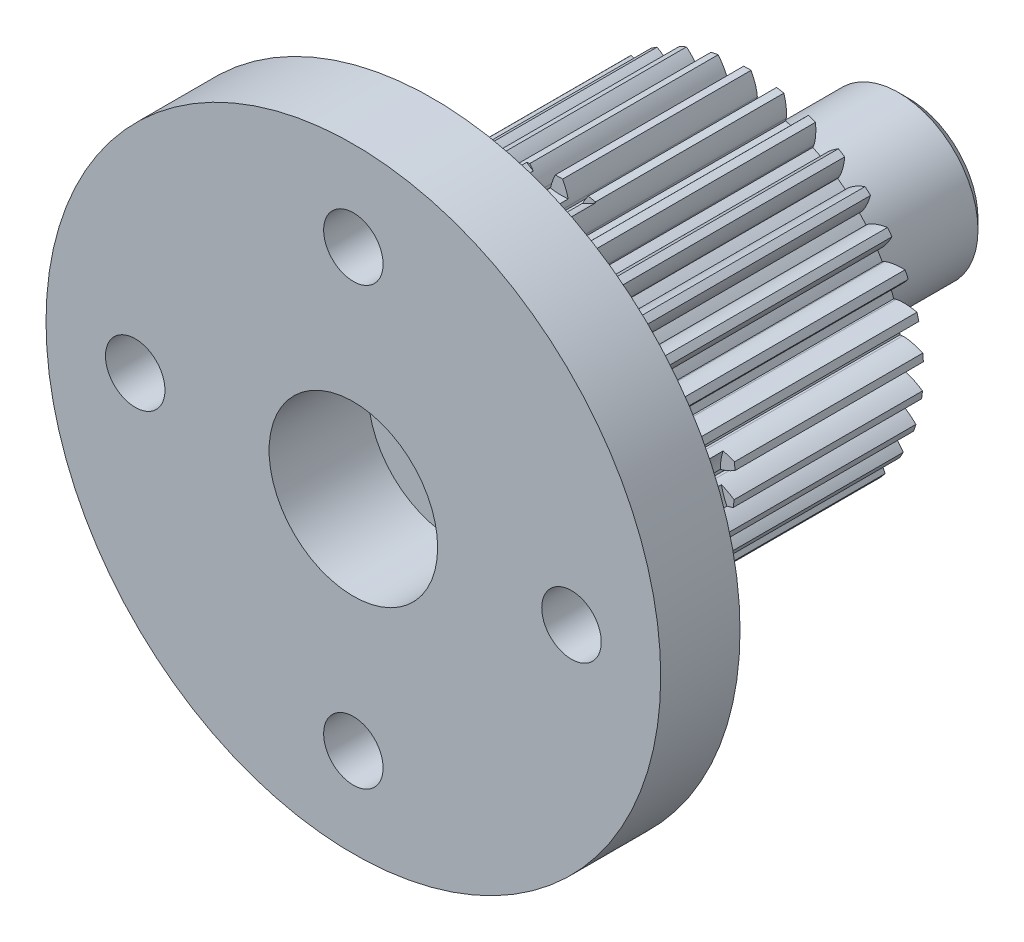
SolidWorks part; units mm, degrees
material "ABS"
ref_plane "Front Plane" through (0, 0, 0) normal (0, 0, 1) x (1, 0, 0)
ref_plane "Top Plane" through (0, 0, 0) normal (0, 1, 0) x (1, 0, 0)
ref_plane "Right Plane" through (0, 0, 0) normal (1, 0, 0) x (0, 0, -1)
sketch "Sketch1" plane through (0, 0, 0) normal (0, 0, 1) x (1, 0, 0)
  circle A0 centre (0, 0) radius 8.75
  dimension "D1" = 17.5
extrude "Boss-Extrude1" add sketch "Sketch1" along normal mid plane 16
sketch "Sketch2" plane through (0, 0, 0) normal (0, 0, 1) x (1, 0, 0)
  line L0 (0, 0) -> (7.7525, 0) construction
  line L1 (0, 0) -> (8.2456, -0.2697) construction
  line L2 (0, 0) -> (7.7359, -0.5066) construction
  line L3 (7.7525, 0) -> (7.625, 0)
  line L4 (7.7359, -0.5066) -> (7.6087, -0.4983)
  circle A0 centre (0, 0) radius 8.25 construction
  circle A1 centre (0, 0) radius 7.7525 construction
  circle A2 centre (0, 0) radius 7.625
  circle A3 centre (0, 0) radius 8.75 construction
  circle A4 centre (0, 0) radius 8.75
  spline S0 degree 4 poles (7.7525, 0) (7.7551, 0) (7.7625, 0.0003) (7.7855, 0.0017) (7.8306, 0.0067) (7.8861, 0.016) (7.9497, 0.0296) (8.0107, 0.045) (8.0626, 0.0595) (8.1142, 0.0754) (8.1654, 0.0924) (8.2271, 0.1143) (8.3008, 0.1426) (8.3862, 0.1784) (8.4823, 0.2223) (8.5793, 0.2706) (8.674, 0.3209) (8.7687, 0.375) (8.8596, 0.4297) (8.9529, 0.4897) (9.0385, 0.5468) (9.1331, 0.6144) (9.2091, 0.67) (9.3078, 0.7471) (9.3656, 0.7937) (9.4328, 0.8496) (9.4624, 0.8751) (9.4806, 0.8908) knots 0 0 0 0 0 0.005377 0.015084 0.04661 0.092111 0.119476 0.146842 0.174209 0.201575 0.228941 0.256307 0.307035 0.361767 0.4165 0.471232 0.525964 0.580697 0.635429 0.690161 0.744894 0.799626 0.854358 0.909091 0.954545 1 1 1 1 1 construction
  spline S1 degree 4 poles (7.7525, 0) (7.7551, 0) (7.7625, 0.0003) (7.7855, 0.0017) (7.8306, 0.0067) (7.8861, 0.016) (7.9497, 0.0296) (8.0107, 0.045) (8.0626, 0.0595) (8.1142, 0.0754) (8.1654, 0.0924) (8.2271, 0.1143) (8.3008, 0.1426) (8.3862, 0.1784) (8.4823, 0.2223) (8.5793, 0.2706) (8.674, 0.3209) (8.7687, 0.375) (8.8596, 0.4297) (8.9529, 0.4897) (9.0385, 0.5468) (9.1331, 0.6144) (9.2091, 0.67) (9.2864, 0.7303) (9.3238, 0.7602) (9.3429, 0.7756) knots 0 0 0 0 0 0.005377 0.015084 0.04661 0.092111 0.119476 0.146842 0.174209 0.201575 0.228941 0.256307 0.307035 0.361767 0.4165 0.471232 0.525964 0.580697 0.635429 0.690161 0.744894 0.799626 0.854358 0.909091 0.909091 0.909091 0.909091 0.909091
  spline S2 degree 4 poles (7.7359, -0.5066) (7.7385, -0.5068) (7.7459, -0.5075) (7.7687, -0.5105) (7.8134, -0.5184) (7.8682, -0.5313) (7.9307, -0.549) (7.9906, -0.5683) (8.0415, -0.5863) (8.0919, -0.6054) (8.1419, -0.6257) (8.2021, -0.6517) (8.2737, -0.6847) (8.3566, -0.726) (8.4496, -0.7761) (8.5433, -0.8306) (8.6345, -0.887) (8.7254, -0.9472) (8.8126, -1.0077) (8.9018, -1.0737) (8.9835, -1.1363) (9.0734, -1.2099) (9.1456, -1.2703) (9.2391, -1.3537) (9.2938, -1.404) (9.3571, -1.4642) (9.385, -1.4915) (9.4021, -1.5084) knots 0 0 0 0 0 0.005377 0.015084 0.04661 0.092111 0.119476 0.146842 0.174209 0.201575 0.228941 0.256307 0.307035 0.361767 0.4165 0.471232 0.525964 0.580697 0.635429 0.690161 0.744894 0.799626 0.854358 0.909091 0.954545 1 1 1 1 1 construction
  spline S3 degree 4 poles (7.7359, -0.5066) (7.7385, -0.5068) (7.7459, -0.5075) (7.7687, -0.5105) (7.8134, -0.5184) (7.8682, -0.5313) (7.9307, -0.549) (7.9906, -0.5683) (8.0415, -0.5863) (8.0919, -0.6054) (8.1419, -0.6257) (8.2021, -0.6517) (8.2737, -0.6847) (8.3566, -0.726) (8.4496, -0.7761) (8.5433, -0.8306) (8.6345, -0.887) (8.7254, -0.9472) (8.8126, -1.0077) (8.9018, -1.0737) (8.9835, -1.1363) (9.0734, -1.2099) (9.1456, -1.2703) (9.2188, -1.3356) (9.2542, -1.3678) (9.2722, -1.3844) knots 0 0 0 0 0 0.005377 0.015084 0.04661 0.092111 0.119476 0.146842 0.174209 0.201575 0.228941 0.256307 0.307035 0.361767 0.4165 0.471232 0.525964 0.580697 0.635429 0.690161 0.744894 0.799626 0.854358 0.909091 0.909091 0.909091 0.909091 0.909091
  dimension "D1" = 16.5
  dimension "D2" = 15.5049
  dimension "D3" = 15.25
  dimension "D4" = 1.873
  dimension "D5" = 1.873
extrude "Cut-Extrude1" cut sketch "Sketch2" against normal through all both and the other way through all contours A2 S3 A4 S1
pattern_circular "CirPattern2" count 33 over 360 about axis through (0, 0, -8) along (0, 0, 1) of "Cut-Extrude1"
sketch "Sketch3" plane through (0, 0, 0) normal (0, 1, 0) x (1, 0, 0)
  line L0 (0, 8) -> (0, 20.841) construction
  line L1 (0, 20.841) -> (0, -26.4333) construction
  line L2 (0, 16) -> (-4, 16)
  line L3 (-4, 16) -> (-4, 9.5)
  line L4 (-4, 9.5) -> (-4.5, 9.5)
  line L6 (-4.5, 9.5) -> (-4.5, 8)
  line L9 (0, 8) -> (-4.5, 8)
  line L10 (1.8277, -8) -> (1.7977, -8) construction
  line L11 (0, -8) -> (-15.5, -8)
  line L12 (-15.5, -8) -> (-15.5, -12)
  line L13 (-15.5, -12) -> (0, -12)
  line L14 (0, 16) -> (0, -12)
  line L15 (2.4114, 8) -> (1.8277, 8) construction
  point P7 (0, -8)
  point P14 (0, 8)
  dimension "D1" = 4
  dimension "D2" = 6.5
  dimension "D3" = 1.5
  dimension "D4" = 0.5
  dimension "D5" = 4
  dimension "D6" = 15.5
revolve "Revolve1" add sketch "Sketch3" angle 360 about L0
chamfer "Chamfer1" distance 0.5 angle 45 1 edges at (4.5, 0, -8)
chamfer "Chamfer2" distance 0.5 angle 45 1 edges at (4, 0, -16)
sketch "Sketch4" plane through (0, 0, 12) normal (0, 0, 1) x (1, 0, 0)
  circle A0 centre (0, 0) radius 2.5
  dimension "D1" = 5
extrude "Cut-Extrude2" cut sketch "Sketch4" against normal through all
sketch "Sketch5" plane through (0, 0, 12) normal (0, 0, 1) x (1, 0, 0)
  circle A0 centre (0, 0) radius 4.25
  dimension "D1" = 8.5
extrude "Cut-Extrude3" cut sketch "Sketch5" against normal blind 5
sketch "Sketch6" plane through (0, 0, 8) normal (0, 0, -1) x (-1, 0, 0)
  circle A0 centre (0, 0) radius 11 construction
  circle A1 centre (0, 11) radius 1.5
  circle A2 centre (11, 0) radius 1.5
  circle A3 centre (0, -11) radius 1.5
  circle A4 centre (-11, 0) radius 1.5
  point P14 (0, 0)
  dimension "D1" = 22
  dimension "D2" = 3
  dimension "D3" = 4
extrude "Cut-Extrude4" cut sketch "Sketch6" against normal through all
sketch "Sketch7" plane through (0, 0, 0) normal (0, 1, 0) x (1, 0, 0)
  line L0 (9.5, -12) -> (12.5, -12) construction
  line L1 (12.5, -8) -> (9.5, -8) construction
  line L2 (9.5, -12) -> (12.5, -12)
  line L4 (11, -8) -> (11, -12) construction
  line L5 (11, -8) -> (14, -8)
  line L6 (14, -8) -> (12.5, -9.5)
  line L7 (12.5, -9.5) -> (11, -9.5)
  line L8 (11, -8) -> (11, -9.5)
  dimension "D3" = 1.5
  dimension "D2" = 3
  dimension "D1" = 1.5
revolve "Cut-Revolve1" cut sketch "Sketch7" angle 360 about L4
pattern_circular "CirPattern3" count 4 over 360 about axis through (0, 0, 0) along (0, 0, 1) of "Cut-Revolve1"
sketch "Sketch8" plane through (0, 0, 8) normal (0, 0, -1) x (-1, 0, 0)
  line L0 (0, 11) -> (0, 0) construction
  circle A0 centre (0, 11) radius 3
  circle A1 centre (0, 0) radius 11 construction
  circle A2 centre (11, 0) radius 3
  circle A3 centre (0, -11) radius 3
  circle A4 centre (-11, 0) radius 3
  point P14 (0, 0)
  dimension "D1" = 22
  dimension "D2" = 6
extrude "Cut-Extrude5" cut sketch "Sketch8" along normal blind 6.5
equation "\"Ns\" = 33"
equation "\"module\" = 0.5"
equation "\"pressure angle\" = 20.0"
equation "\"h_a\" = 0.5"
equation "\"h_b\" = 0.625"
equation "\"clr_tip_root\" = 0.125"
equation "\"dp_s\" = 16.5"
equation "\"db_s\" = 15.50492824296749"
equation "\"D1@Sketch1\"=\"dp_s\" + 2*\"h_a\""
equation "\"fw_s_calc\" = 1.2595130854287364"
equation "\"D1@Boss-Extrude1\"=\"fw_s_used\""
equation "\"D1@Sketch2\"=\"dp_s\""
equation "\"D2@Sketch2\"= \"db_s\""
equation "\"D3@Sketch2\"=\"dp_s\"- 2*\"h_b\""
equation "\"alpha_s\" = 0.8539582918412449"
equation "\"D4@Sketch2\"= 360 / ( 4 * \"Ns\" ) - \"alpha_s\""
equation "\"beta_s\" = 3.7466288708629643"
equation "\"D5@Sketch2\"= 360 / ( 4 * \"Ns\" ) - \"alpha_s\""
equation "\"D1@CirPattern2\"=\"Ns\""
equation "\"Np\" = 45"
equation "\"dp_p\" = 22.5"
equation "\"db_p\" = 21.14308396768294"
equation "\"fw_p\" = 8.0"
equation "\"alpha_p\" = 0.8539582918412307"
equation "\"beta_p\" = 2.2920834163175385"
equation "\"Nr\" = 123"
equation "\"pressure_angle\" = 20.0"
equation "\"h_f\" = 0.625"
equation "\"dp_r\" = 61.5"
equation "\"db_r\" = 57.79109617833337"
equation "\"fw_r\" = 8.0"
equation "\"alpha_r\" = 0.8539582918412414"
equation "\"beta_r\" = 3.171331217828824"
equation "\"bearing_ID\" = 50"
equation "\"bearing_OD\" = 65"
equation "\"bearing_height\" = 7"
equation "\"clearance_planet\" = 1.5"
equation "\"case_dist\" = 6.5"
equation "\"Motor_case_OD_max\" = 96.5"
equation "\"case_mounting_PCD\" = 89.0"
equation "\"bearing mount thickness\" = 8"
equation "\"case_mounting_hole_dia\" = 3"
equation "\"output_mounting_PCD\" = 73"
equation "\"output_mounting_hole_dia\" = 4"
equation "\"clearance_case_mount_holes_shell_thickness\" = 1"
equation "\"motor_case_OD_base\" = 87.0"
equation "\"sec_carrier_thickness\" = 5"
equation "\"sun_coupler_hub_thickness\" = 4"
equation "\"clearance_sun_coupler_sec_carrier\" = 1.5"
equation "\"clearance_motor_and_case\" = 5"
equation "\"motor_OD\" = 72"
equation "\"Motor_case_thickness\" = 2.5"
equation "\"Motor_case_ID\" = 82"
equation "\"case_mounting_hole_shift\" = 1.0"
equation "\"output_mounting_nut_wrench_size\" = 7"
equation "\"output_mounting_nut_thickness\" = 3.2"
equation "\"case_mounting_hole_allen_socket_dia\" = 5.5"
equation "\"output_mounting_nut_depth\" = 3"
equation "\"case_mounting_bolt_depth\" = 4.5"
equation "\"ring_radial_thickness\" = 5"
equation "\"ring_OD\" = 71.5"
equation "\"ring_to_chamfer_clearance\" = 2"
equation "\"Motor_case_OD_base_to_chamfer\" = 5"
equation "\"pattern_offset_from_motor_case_OD_base\" = 3"
equation "\"pattern_bulge_dia\" = 3"
equation "\"pattern_num_bulge\" = 18"
equation "\"pattern_depth\" = 2"
equation "\"motor_height\" = 27"
equation "\"case_mounting_wrench_size\" = 5.5"
equation "\"case_mounting_nut_clearance\" = 2"
equation "\"base_plate_thickness\" = 4"
equation "\"case_mounting_nut_thickness\" = 2.4"
equation "\"case_mounting_surface_height\" = 4"
equation "\"motor_mount_hole_PCD\" = 32"
equation "\"motor_mount_hole_dia\" = 4"
equation "\"motor_mount_hole_num\" = 4"
equation "\"central_hole_offset_from_motor_mount_PCD\" = 5"
equation "\"wire_slot_dist_from_center\" = 30"
equation "\"wire_slot_length\" = 10"
equation "\"wire_slot_radius\" = 2.5"
equation "\"driver_upper_holes_dist_from_center\" = 23"
equation "\"driver_lower_holes_dist_from_center\" = 15"
equation "\"driver_side_holes_dist_from_center\" = 20"
equation "\"driver_mount_holes_dia\" = 2.5"
equation "\"driver_mount_inserts_OD\" = 3.5"
equation "\"driver_mount_thickness\" = 1.5"
equation "\"driver_mount_height\" = 4"
equation "\"air_flow_hole_offset\" = 3"
equation "\"num_planet\" = 3"
equation "\"planet_pin_bolt_dia\" = 5"
equation "\"planet_pin_socket_head_dia\" = 8.5"
equation "\"carrier_PCD\" = 39.0"
equation "\"planet_shaft_dia\" = 8"
equation "\"planet_shaft_step_offset\" = 1"
equation "\"carrier_trapezoidal_support_sun_offset\" = 5"
equation "\"carrier_trapezoidal_support_hole_PCD_offset_bearing_ID\" = 4"
equation "\"carrier_trapezoidal_support_hole_dia\" = 3"
equation "\"carrier_trapezoidal_support_hole_socket_head_dia\" = 5.5"
equation "\"carrier_bearing_step_width\" = 1.5"
equation "\"standard_clearance_1_5mm\" = 1.5"
equation "\"standard_fillet_1_5mm\" = 1.5"
equation "\"sun_shaft_bearing_OD\" = 16"
equation "\"sun_shaft_bearing_width\" = 5"
equation "\"standard_bearing_insertion_chamfer\" = 0.5"
equation "\"carrier_trapezoidal_support_hole_wrench_size\" = 5.5"
equation "\"planet_pin_bolt_wrench_size\" = 8"
equation "\"planet_bearing_OD\" = 12"
equation "\"planet_bearing_width\" = 3.5"
equation "\"planet_bore\" = 10"
equation "\"motor_output_hole_PCD\" = 22"
equation "\"motor_output_hole_dia\" = 3"
equation "\"motor_output_hole_num\" = 4"
equation "\"sun_shaft_bearing_ID\" = 8"
equation "\"D1@Sketch3\"=\"sun_shaft_bearing_ID\"/2"
equation "\"D2@Sketch3\"=\"sun_shaft_bearing_width\" + \"standard_clearance_1_5mm\""
equation "\"D3@Sketch3\"=\"standard_clearance_1_5mm\""
equation "\"D4@Sketch3\"=\"standard_clearance_1_5mm\"/3"
equation "\"D5@Sketch3\"=\"sun_coupler_hub_thickness\""
equation "\"sun_hub_dia\" = 31.0"
equation "\"D6@Sketch3\"=\"sun_hub_dia\"/2"
equation "\"D1@Chamfer2\"=\"standard_bearing_insertion_chamfer\""
equation "\"D1@Chamfer1\"=\"standard_bearing_insertion_chamfer\""
equation "\"sun_central_bolt_dia\" = 5"
equation "\"sun_central_bolt_socket_head_dia\" = 8.5"
equation "\"D1@Sketch4\"=\"sun_central_bolt_dia\""
equation "\"D1@Cut-Extrude3\"=\"sun_central_bolt_dia\""
equation "\"D1@Sketch5\"=\"sun_central_bolt_socket_head_dia\""
equation "\"fw_s_used\" = 16.0"
equation "\"D1@Sketch6\"=\"motor_output_hole_PCD\""
equation "\"D2@Sketch6\"=\"motor_output_hole_dia\""
equation "\"D3@Sketch6\"=\"motor_output_hole_num\""
equation "\"motor_output_hole_CSK_OD\" = 6"
equation "\"motor_output_hole_CSK_head_height\" = 1.5"
equation "\"D2@Sketch7\"=\"motor_output_hole_CSK_OD\"/2"
equation "\"D3@Sketch7\"=\"motor_output_hole_dia\"/2"
equation "\"D1@CirPattern3\"=\"motor_output_hole_num\""
equation "\"D1@Sketch7\"=\"motor_output_hole_CSK_head_height\""
equation "\"D1@Sketch8\"=\"motor_output_hole_PCD\""
equation "\"D2@Sketch8\"=\"motor_output_hole_CSK_OD\""
equation "\"D1@Cut-Extrude5\"=\"sec_carrier_thickness\"+\"standard_clearance_1_5mm\""
equation "\"Cut-Extrude5\"= IIF ( ( \"Ns\" * \"module\" + 2 * \"h_a\" ) < ( \"motor_output_hole_PCD\" - \"motor_output_hole_CSK_OD\" ) , \"suppressed\" , \"unsuppressed\" )"
equation "\"bearing_retainer_thickness\" = 2"
